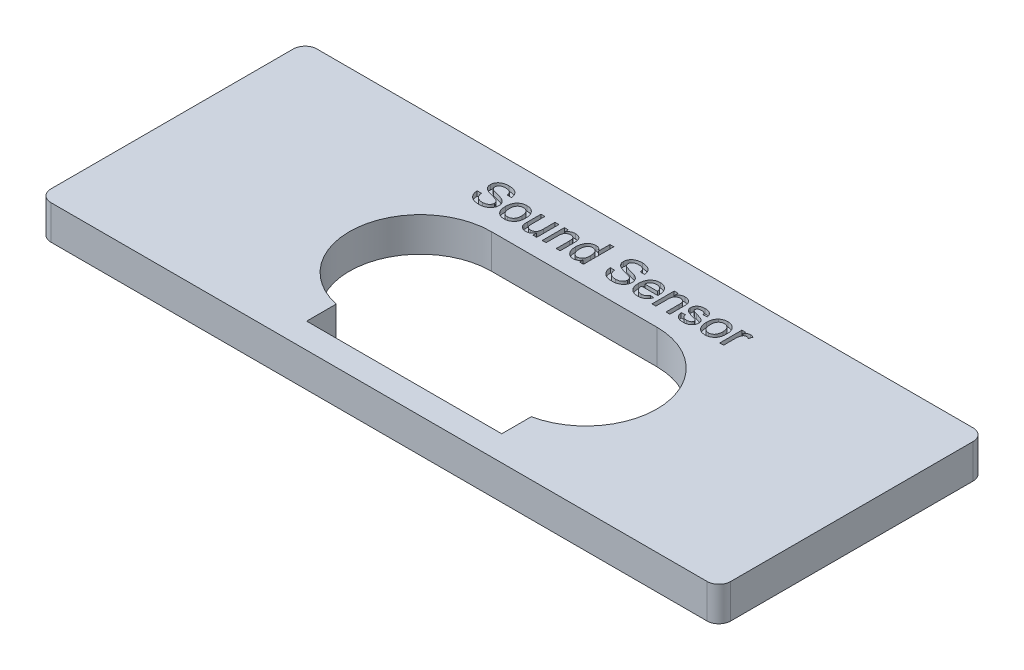
SolidWorks part; units mm, degrees
material "ABS"
ref_plane "Front Plane" through (0, 0, 0) normal (0, 0, 1) x (1, 0, 0)
ref_plane "Top Plane" through (0, 0, 0) normal (0, 1, 0) x (1, 0, 0)
ref_plane "Right Plane" through (0, 0, 0) normal (1, 0, 0) x (0, 0, -1)
sketch "Sketch1" plane through (0, 0, 0) normal (0, 1, 0) x (1, 0, 0)
  line L1 (1, 0) -> (56.5, 0)
  line L2 (0, 1) -> (0, 21.5)
  line L3 (1, 22.5) -> (56.5, 22.5)
  line L4 (57.5, 1) -> (57.5, 21.5)
  arc A0 (56.5, 22.5) -> (57.5, 21.5) centre (56.5, 21.5) cw
  arc A1 (57.5, 1) -> (56.5, 0) centre (56.5, 1) cw
  arc A2 (1, 0) -> (0, 1) centre (1, 1) cw
  arc A3 (0, 21.5) -> (1, 22.5) centre (1, 21.5) cw
  point P11 (0, 0)
  dimension "D1" = 1
extrude "Boss-Extrude1" add sketch "Sketch1" along normal blind 2.9
ref_plane "Plane1" through (0, 3, 0) normal (0, 1, 0) x (1, 0, 0)
sketch "Sketch2" plane through (0, 3, 0) normal (0, 1, 0) x (1, 0, 0)
  line L0 (0, 0) -> (0, 1.5)
  line L1 (0, 21.5) -> (0, 1) construction
  line L2 (0, 1.5) -> (1.5, 1.5)
  line L3 (35.75, 0) -> (35.75, 1.5)
  line L4 (35.75, 22.5) -> (35.75, 21)
  line L6 (21.75, 10.5) -> (35.75, 10.5) construction
  line L9 (56.5, 22.5) -> (1, 22.5) construction
  line L10 (21.75, 16.5) -> (35.75, 16.5)
  line L11 (21.75, 4.5) -> (35.75, 4.5)
  line L12 (1, 0) -> (56.5, 0) construction
  arc A2 (21.75, 16.5) -> (21.75, 4.5) centre (21.75, 10.5) ccw
  arc A3 (35.75, 4.5) -> (35.75, 16.5) centre (35.75, 10.5) ccw
  point P13 (28.75, 10.5)
extrude "Cut-Extrude1" cut sketch "Sketch2" against normal blind 10
sketch "Sketch4" plane through (0, 3, 0) normal (0, 1, 0) x (1, 0, 0)
  text T0 "Sound Sensor" font "Century Gothic" height in points 10
  point P1 (18.1887, 17.234)
  point P2 (0, 0)
extrude "Cut-Extrude2" cut sketch "Sketch4" against normal blind 0.5
sketch "Sketch5" plane through (0, 3, 0) normal (0, 1, 0) x (1, 0, 0)
  line L2 (28.75, 2.1317) -> (37, 2.1317)
  line L3 (28.75, 2.1317) -> (20.5, 2.1317)
  line L4 (20.5, 2.1317) -> (20.5, 4.6317)
  line L5 (37, 2.1317) -> (37, 4.6317)
  line L6 (20.5, 4.6317) -> (37, 4.6317)
  arc A0 (21.75, 16.5) -> (21.75, 4.5) centre (21.75, 10.5) ccw construction
  arc A1 (35.75, 4.5) -> (35.75, 16.5) centre (35.75, 10.5) ccw construction
extrude "Cut-Extrude3" cut sketch "Sketch5" against normal blind 10
